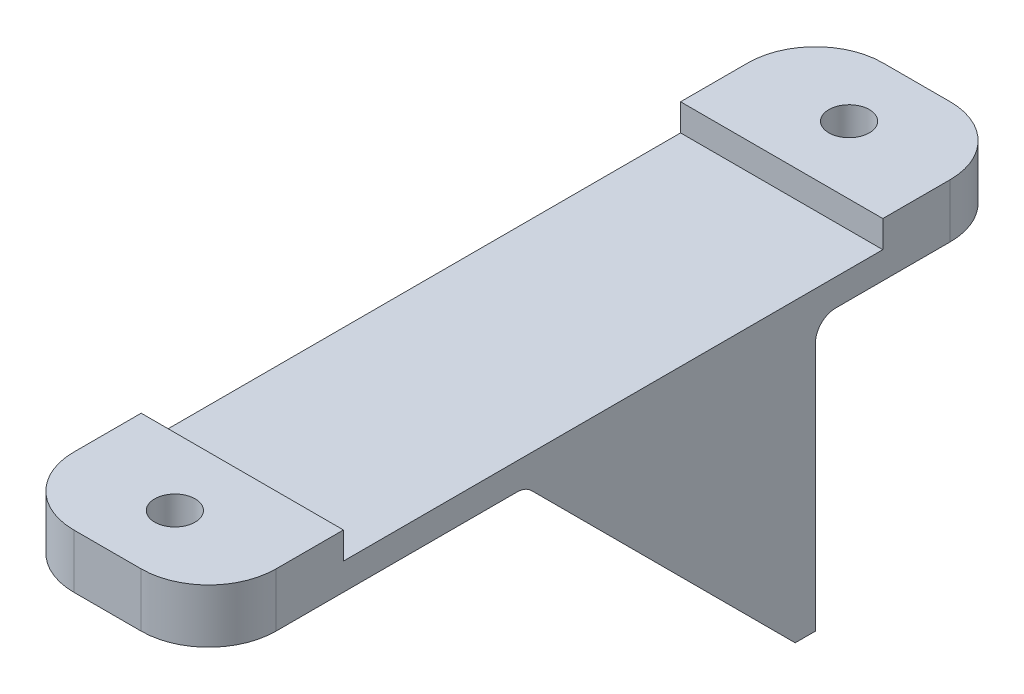
SolidWorks part; units mm, degrees
ref_plane "Front Plane" through (0, 0, 0) normal (0, 0, 1) x (1, 0, 0)
ref_plane "Top Plane" through (0, 0, 0) normal (0, 1, 0) x (1, 0, 0)
ref_plane "Right Plane" through (0, 0, 0) normal (1, 0, 0) x (0, 0, -1)
sketch "Sketch1" plane through (0, 0, 0) normal (0, 1, 0) x (1, 0, 0)
  line L1 (0, 0) -> (30, 0)
  line L2 (0, 0) -> (0, 120)
  line L3 (0, 120) -> (30, 120)
  line L4 (30, 0) -> (30, 120)
  dimension "D1" = 120
  dimension "D2" = 30
extrude "Boss-Extrude1" add sketch "Sketch1" along normal blind 8
sketch "Sketch2" plane through (0, 8, 0) normal (0, 1, 0) x (1, 0, 0)
  line L0 (0, 120) -> (0, 0) construction
  line L1 (30, 100) -> (0, 100)
  line L2 (30, 100) -> (30, 20)
  line L3 (30, 20) -> (0, 20)
  line L4 (0, 100) -> (0, 20)
  line L5 (30, 100) -> (0, 20) construction
  line L6 (30, 20) -> (0, 100) construction
  line L7 (30, 120) -> (0, 120) construction
  point P0 (15, 60)
  dimension "D1" = 80
  dimension "D2" = 30
  dimension "D3" = 20
extrude "Cut-Extrude1" cut sketch "Sketch2" against normal blind 4
sketch "Sketch3" plane through (0, 0, 0) normal (0, -1, 0) x (1, 0, 0)
  line L0 (0, -120) -> (0, 0) construction
  line L1 (0, -87) -> (30, -87)
  line L2 (0, -87) -> (0, -90)
  line L3 (0, -90) -> (30, -90)
  line L4 (30, -87) -> (30, -90)
  line L5 (30, 0) -> (30, -120) construction
  line L7 (30, -120) -> (0, -120) construction
  dimension "D1" = 30
  dimension "D2" = 3
extrude "Boss-Extrude2" add sketch "Sketch3" along normal blind 40
sketch "Sketch4" plane through (0, 0, -87) normal (0, 0, 1) x (1, 0, 0)
  line L0 (30, -40) -> (0, -40) construction
  line L1 (0, -40) -> (0, 0) construction
  circle A0 centre (15, -20) radius 8.75
  dimension "D2" = 17.5
  dimension "D3" = 15
  dimension "D1" = 20
extrude "Cut-Extrude2" cut sketch "Sketch4" against normal blind 40
sketch "Sketch5" plane through (30, 0, 0) normal (1, 0, 0) x (0, 0, -1)
  line L0 (87, -40) -> (47, 0)
  line L1 (0, 0) -> (87, 0) construction
  line L3 (87, 0) -> (87, -40)
  line L4 (47, 0) -> (87, 0)
  dimension "D1" = 45
extrude "Boss-Extrude3" add sketch "Sketch5" against normal blind 2.5
sketch "Sketch6" plane through (0, 0, 0) normal (-1, 0, 0) x (0, 0, 1)
  line L0 (-47, 0) -> (-87, -40) construction
  line L1 (-87, 0) -> (0, 0) construction
  line L2 (-87, -40) -> (-87, 0) construction
  line L3 (-47, 0) -> (-87, -40)
  line L4 (-87, 0) -> (-47, 0)
  line L5 (-87, -40) -> (-87, 0)
extrude "Boss-Extrude4" add sketch "Sketch6" against normal blind 2.5
sketch "Sketch7" plane through (0, 0, 0) normal (0, -1, 0) x (-1, 0, 0)
  line L0 (-30, 0) -> (-30, 47) construction
  line L1 (0, 0) -> (-30, 0) construction
  line L2 (-30, 120) -> (0, 120) construction
  line L3 (0, 120) -> (0, 90) construction
  circle A0 centre (-15, 10) radius 3
  circle A1 centre (-15, 110) radius 3
  dimension "D3" = 6
  dimension "D4" = 6
  dimension "D5" = 10
  dimension "D6" = 15
  dimension "D1" = 15
  dimension "D2" = 10
extrude "Cut-Extrude3" cut sketch "Sketch7" against normal through all
fillet "Fillet1" radius 10 4 edges at (30, 4, -120) (0, 4, -120) (30, 4, 0) (0, 4, 0)
fillet "Fillet2" radius 3 1 edges at (15, 0, -90)
fillet "Fillet3" radius 3 2 edges at (28.75, 0, -47) (1.25, 0, -47)
